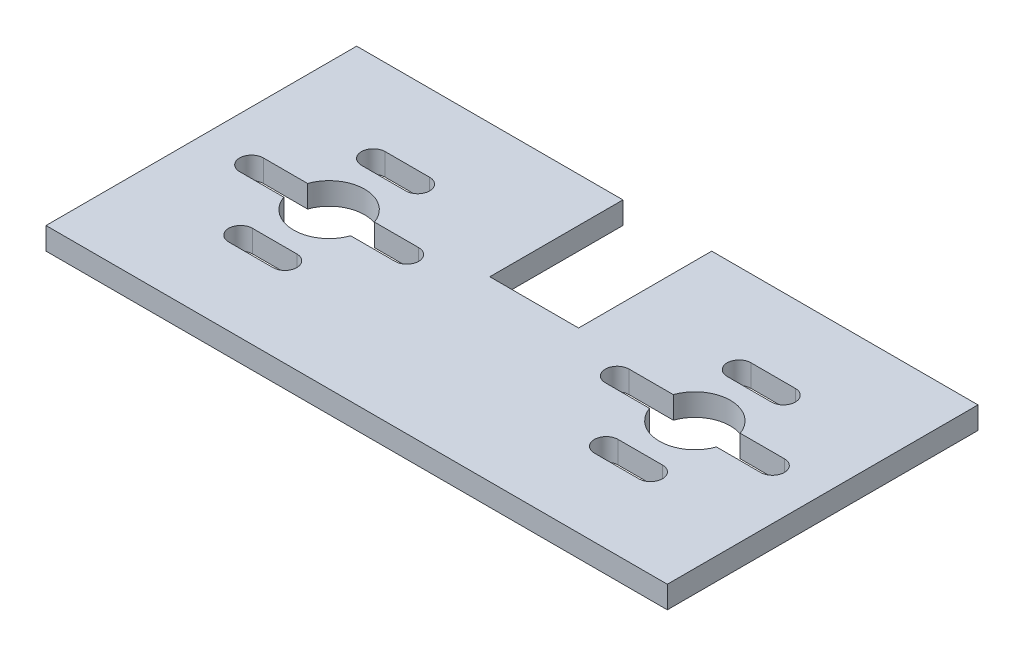
SolidWorks part; units mm, degrees
ref_plane "Front Plane" through (0, 0, 0) normal (0, 0, 1) x (1, 0, 0)
ref_plane "Top Plane" through (0, 0, 0) normal (0, 1, 0) x (1, 0, 0)
ref_plane "Right Plane" through (0, 0, 0) normal (1, 0, 0) x (0, 0, -1)
sketch "Sketch1" plane through (0, 0, 0) normal (0, 1, 0) x (1, 0, 0)
  line L1 (-44.45, 22.225) -> (44.45, 22.225)
  line L2 (-44.45, 22.225) -> (-44.45, -22.225)
  line L3 (-44.45, -22.225) -> (44.45, -22.225)
  line L4 (44.45, 22.225) -> (44.45, -22.225)
  line L5 (-44.45, 22.225) -> (44.45, -22.225) construction
  line L6 (-44.45, -22.225) -> (44.45, 22.225) construction
  point P0 (0, 0)
  dimension "D1" = 44.45
  dimension "D2" = 88.9
extrude "Boss-Extrude1" add sketch "Sketch1" along normal blind 3.175
sketch "Sketch3" plane through (0, 0, 0) normal (0, -1, 0) x (1, 0, 0)
  line L0 (-19.7611, 9.5) -> (49980.2389, 9.5) construction
  line L1 (-38.9143, -9.5) -> (49961.0857, -9.5) construction
  line L2 (22.5615, 0) -> (-22.5615, 0) construction
  line L4 (-22.9888, 9.5) -> (-29.3388, 9.5) construction
  line L5 (-22.9888, 7.8) -> (-29.3388, 7.8)
  line L6 (-22.9888, 11.2) -> (-29.3388, 11.2)
  line L7 (0, -11.25) -> (0, 12.95) construction
  line L8 (-29.3388, -9.5) -> (-22.9888, -9.5) construction
  line L9 (-29.3388, -7.8) -> (-22.9888, -7.8)
  line L10 (-29.3388, -11.2) -> (-22.9888, -11.2)
  line L11 (-37.2763, 0) -> (-15.0513, 0) construction
  line L12 (-37.2763, 1.7) -> (-15.0513, 1.7)
  line L13 (-37.2763, -1.7) -> (-15.0513, -1.7)
  circle A6 centre (-26.1638, 0) radius 5.08
  arc A7 (-22.9888, 7.8) -> (-22.9888, 11.2) centre (-22.9888, 9.5) ccw
  arc A8 (-29.3388, 11.2) -> (-29.3388, 7.8) centre (-29.3388, 9.5) ccw
  arc A9 (-29.3388, -7.8) -> (-29.3388, -11.2) centre (-29.3388, -9.5) ccw
  arc A10 (-22.9888, -11.2) -> (-22.9888, -7.8) centre (-22.9888, -9.5) ccw
  arc A11 (-37.2763, 1.7) -> (-37.2763, -1.7) centre (-37.2763, 0) ccw
  arc A12 (-15.0513, -1.7) -> (-15.0513, 1.7) centre (-15.0513, 0) ccw
  point P12 (-26.1638, -9.5)
  point P20 (-26.1638, 9.5)
  point P30 (-26.1638, 0)
  point P36 (0, 0)
  point P37 (-24.4539, 2.3359)
  point P38 (-25.9869, 0)
  point P39 (0, 0)
  point P40 (0, 0)
  dimension "D3" = 26.1638
  dimension "D7" = 10.16
  dimension "D1" = 19
  dimension "D2" = 9.5
  dimension "D4" = 3.4
  dimension "D5" = 3.4
  dimension "D6" = 22.225
  dimension "D8" = 3.4
  dimension "D9" = 6.35
extrude "Cut-Extrude1" cut sketch "Sketch3" against normal through all contours L6 A8 L5 A7 | L12 A11 L13 A6 | L13 A6 L12 | L12 A6 | L13 A12 L12 A6 | L13 A6 | L10 A10 L9 A9
mirror "Mirror1" about plane through (0, 0, 0) normal (1, 0, 0) of "Cut-Extrude1"
sketch "Sketch7" plane through (0, 3.175, 0) normal (0, 1, 0) x (1, 0, 0)
  line L5 (44.45, 22.225) -> (-44.45, 22.225) construction
  line L6 (-6.35, 22.225) -> (6.35, 22.225)
  line L7 (-6.35, 22.225) -> (-6.35, 3.175)
  line L8 (-6.35, 3.175) -> (6.35, 3.175)
  line L9 (6.35, 22.225) -> (6.35, 3.175)
  point P6 (0, 3.175)
  dimension "D1" = 12.7
  dimension "D2" = 19.05
extrude "Cut-Extrude2" cut sketch "Sketch7" against normal through all
